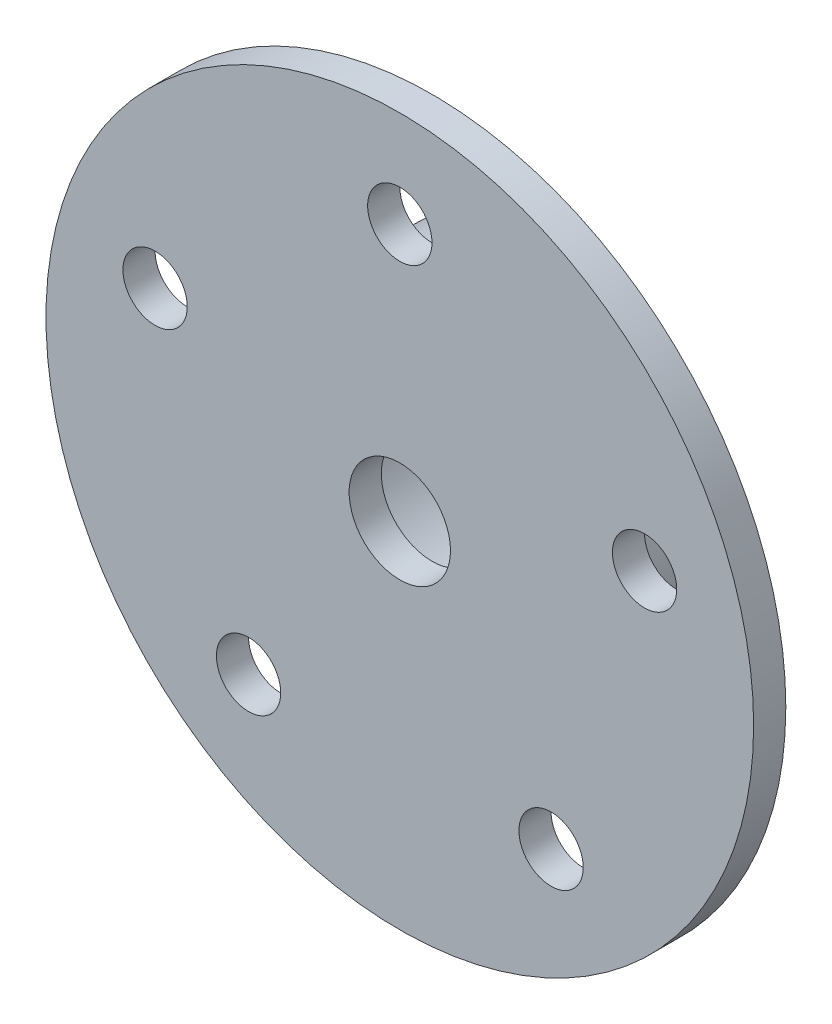
SolidWorks part; units mm, degrees
ref_plane "前视基准面" through (0, 0, 0) normal (0, 0, 1) x (1, 0, 0)
ref_plane "上视基准面" through (0, 0, 0) normal (0, 1, 0) x (1, 0, 0)
ref_plane "右视基准面" through (0, 0, 0) normal (1, 0, 0) x (0, 0, -1)
other "Configuration Table"
sketch "草图1" plane through (0, 0, 0) normal (0, 0, 1) x (1, 0, 0)
  circle A4 centre (0, 0) radius 3.15
  circle A5 centre (0, 0) radius 22
  circle A6 centre (0, 0) radius 16 construction
  circle A8 centre (0, 16) radius 2
  circle A9 centre (15.2169, 4.9443) radius 2
  circle A10 centre (9.4046, -12.9443) radius 2
  circle A11 centre (-9.4046, -12.9443) radius 2
  circle A12 centre (-15.2169, 4.9443) radius 2
  point P0 (0, 0)
  point P17 (0, 0)
  point P19 (0, 0)
  dimension "D3" = 5
  dimension "D5" = 4
  dimension "D1" = 44
  dimension "D2" = 32
  dimension "D4" = 6.3
extrude "凸台-拉伸1" add sketch "草图1" along normal blind 2
sketch "草图3" plane through (0, 0, 0) normal (0, 0, -1) x (-1, 0, 0)
  circle A0 centre (0, 0) radius 11
  circle A1 centre (0, 0) radius 7.6
  dimension "D1" = 22
  dimension "D2" = 15.2
extrude "凸台-拉伸2" add sketch "草图3" along normal blind 7
